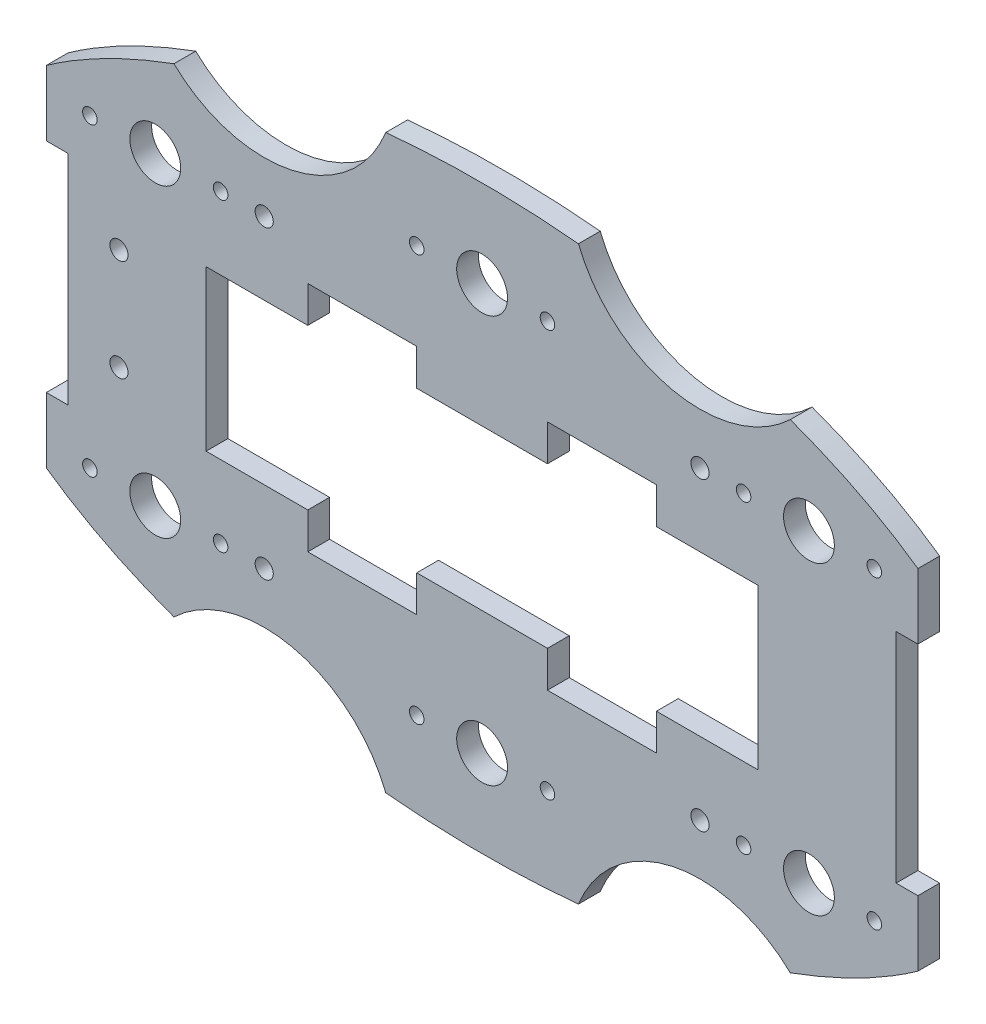
SolidWorks part; units mm, degrees
ref_plane "Front Plane" through (0, 0, 0) normal (0, 0, 1) x (1, 0, 0)
ref_plane "Top Plane" through (0, 0, 0) normal (0, 1, 0) x (1, 0, 0)
ref_plane "Right Plane" through (0, 0, 0) normal (1, 0, 0) x (0, 0, -1)
sketch "Sketch1" plane through (0, 0, 0) normal (0, 0, 1) x (1, 0, 0)
  line L0 (0, 58.0261) -> (0, -57.1812) construction
  line L1 (-90.1861, 0) -> (91.195, 0) construction
  line L2 (-82.1585, 35) -> (79.479, 35) construction
  line L3 (-82.1585, -35) -> (79.479, -35) construction
  line L4 (-26.1342, 28) -> (23.6542, 28) construction
  line L5 (-45, 40.2551) -> (-45, -60.8173) construction
  line L6 (45, 41.6447) -> (45, -60.8173) construction
  circle A0 centre (0, 28) radius 3.5
  circle A1 centre (0, -28) radius 3.5
  circle A2 centre (45, 21) radius 3.5
  circle A3 centre (-45, 21) radius 3.5
  circle A4 centre (-45, -21) radius 3.5
  circle A5 centre (45, -21) radius 3.5
  ellipse E0 centre (0, 0) end of major axis (75, 0) minor radius 40
  dimension "D6" = 0
  dimension "D7" = 7
  dimension "D11" = 7
  dimension "D12" = 14
  dimension "D13" = 14
  dimension "D14" = 7
  dimension "D15" = 7
  dimension "D16" = 7
  dimension "D17" = 7
  dimension "D18" = 14
  dimension "D19" = 14
  dimension "D1" = 80
  dimension "D2" = 150
  dimension "D3" = 35
  dimension "D4" = 35
  dimension "D5" = 12
  dimension "D8" = 45
  dimension "D9" = 45
  dimension "D10" = 12
extrude "Boss-Extrude1" add sketch "Sketch1" along normal blind 3
sketch "Sketch2" plane through (0, 0, 3) normal (0, 0, 1) x (1, 0, 0)
  line L0 (-45, 21) -> (45, 21) construction
  line L1 (0, 50.348) -> (0, -52.915) construction
  line L2 (-45, -21) -> (45, -21) construction
  line L3 (60, 24) -> (60, 15)
  line L4 (-60, 24) -> (-60, 15)
  line L5 (30, 52.9537) -> (30, -58.0622) construction
  line L6 (60, 15) -> (57, 15)
  line L8 (60, -15) -> (57, -15)
  line L9 (57, 15) -> (57, -15)
  line L10 (-60, 15) -> (-57, 15)
  line L11 (60, -15) -> (60, -24)
  line L12 (-60, -15) -> (-57, -15)
  line L13 (-57, 15) -> (-57, -15)
  line L14 (-30, 52.9537) -> (-30, -58.0622) construction
  line L15 (-60, -15) -> (-60, -24)
  circle A0 centre (-30, 21) radius 1.25
  circle A1 centre (30, 21) radius 1.25
  circle A2 centre (30, -21) radius 1.25
  circle A3 centre (-30, -21) radius 1.25
  circle A5 centre (30, 46) radius 18
  circle A6 centre (-30, 46) radius 18
  circle A7 centre (30, -46) radius 18
  circle A8 centre (-30, -46) radius 18
  ellipse E0 centre (0, 0) end of major axis (75, 0) minor radius 40 construction
  ellipse E1 centre (0, 0) end of major axis (75, 0) minor radius 40 (-60, 24) -> (-60, -24) ccw
  ellipse E2 centre (0, 0) end of major axis (75, 0) minor radius 40 (60, -24) -> (60, 24) ccw
  dimension "D1" = 2.5
  dimension "D2" = 30
  dimension "D4" = 30
  dimension "D5" = 30
  dimension "D7" = 15
  dimension "D12" = 25
  dimension "D13" = 25
  dimension "D14" = 25
  dimension "D15" = 25
  dimension "D16" = 36
  dimension "D3" = 30
  dimension "D6" = 15
  dimension "D8" = 3
  dimension "D9" = 30
  dimension "D10" = 30
  dimension "D11" = 3
extrude "Cut-Extrude1" cut sketch "Sketch2" against normal blind 10
sketch "Sketch4" plane through (0, 0, 3) normal (0, 0, 1) x (1, 0, 0)
  line L0 (0, 47.3474) -> (0, -46.2459) construction
  line L1 (-64.0978, 0) -> (70.251, 0) construction
  line L2 (-9, 11) -> (9, 11)
  line L3 (-38, -11) -> (-24, -11)
  line L4 (-38, -11) -> (-38, 11)
  line L5 (-38, 11) -> (-24, 11)
  line L6 (38, -11) -> (38, 11)
  line L7 (-38, -11) -> (38, 11) construction
  line L8 (-38, 11) -> (38, -11) construction
  line L9 (-9, -11) -> (9, -11)
  line L10 (9, -11) -> (9, -16)
  line L11 (9, -16) -> (24, -16)
  line L12 (24, -11) -> (24, -16)
  line L13 (24, -11) -> (38, -11)
  line L14 (9, 11) -> (9, 16)
  line L15 (9, 16) -> (24, 16)
  line L16 (24, 11) -> (24, 16)
  line L17 (24, 11) -> (38, 11)
  line L18 (-24, 11) -> (-24, 16)
  line L19 (-24, 16) -> (-9, 16)
  line L20 (-9, 11) -> (-9, 16)
  line L21 (-10.6108, 28) -> (11.5435, 28) construction
  line L22 (-24, -11) -> (-24, -16)
  line L23 (-24, -16) -> (-9, -16)
  line L24 (-9, -11) -> (-9, -16)
  line L25 (-16.1631, -28) -> (16.9678, -28) construction
  line L26 (35.062, 21) -> (53.9927, 21) construction
  line L27 (33.2455, -21) -> (55.8407, -21) construction
  line L28 (-55.3535, 21) -> (-34.9139, 21) construction
  line L29 (-53.586, -21) -> (-34.9139, -21) construction
  circle A0 centre (9, 28) radius 1
  circle A1 centre (-9, 28) radius 1
  circle A2 centre (0, 28) radius 3.5 construction
  circle A3 centre (9, -28) radius 1
  circle A4 centre (-9, -28) radius 1
  circle A5 centre (0, -28) radius 3.5 construction
  circle A7 centre (54, 21) radius 1
  circle A8 centre (36, 21) radius 1
  circle A9 centre (45, 21) radius 3.5 construction
  circle A10 centre (54, -21) radius 1
  circle A11 centre (36, -21) radius 1
  circle A12 centre (45, -21) radius 3.5 construction
  circle A13 centre (-36, 21) radius 1
  circle A14 centre (-54, 21) radius 1
  circle A15 centre (-45, 21) radius 3.5 construction
  circle A16 centre (-36, -21) radius 1
  circle A17 centre (-54, -21) radius 1
  circle A18 centre (-45, -21) radius 3.5 construction
  point P5 (0, 0)
  dimension "D9" = 2
  dimension "D10" = 2
  dimension "D11" = 9
  dimension "D12" = 9
  dimension "D13" = 2
  dimension "D14" = 2
  dimension "D15" = 9
  dimension "D16" = 9
  dimension "D17" = 2
  dimension "D18" = 2
  dimension "D19" = 9
  dimension "D20" = 9
  dimension "D21" = 2
  dimension "D22" = 2
  dimension "D23" = 9
  dimension "D24" = 9
  dimension "D25" = 2
  dimension "D26" = 2
  dimension "D27" = 9
  dimension "D28" = 9
  dimension "D29" = 2
  dimension "D30" = 2
  dimension "D31" = 9
  dimension "D32" = 9
  dimension "D1" = 22
  dimension "D2" = 76
  dimension "D3" = 15
  dimension "D4" = 5
  dimension "D5" = 14
  dimension "D6" = 14
  dimension "D7" = 14
  dimension "D8" = 14
extrude "Cut-Extrude2" cut sketch "Sketch4" against normal blind 10
sketch "Sketch9" plane through (0, 0, 0) normal (0, 0, -1) x (-1, 0, 0)
  line L0 (8.4732, 0) -> (78.2362, 0) construction
  line L1 (50, 13.8838) -> (50, -16.0491) construction
  circle A0 centre (50, 7) radius 1.25
  circle A1 centre (50, -7) radius 1.25
  dimension "D2" = 2.5
  dimension "D3" = 14
  dimension "D4" = 7
  dimension "D1" = 50
extrude "Cut-Extrude3" cut sketch "Sketch9" against normal blind 3
